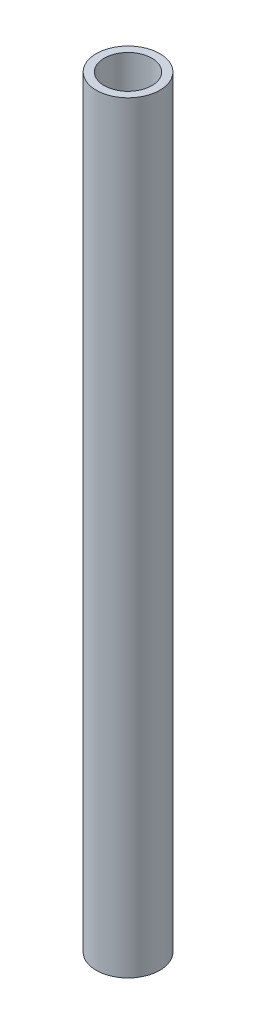
SolidWorks part; units mm, degrees
ref_plane "Front" through (0, 0, 0) normal (0, 0, 1) x (1, 0, 0)
ref_plane "Top" through (0, 0, 0) normal (0, 1, 0) x (1, 0, 0)
ref_plane "Right" through (0, 0, 0) normal (1, 0, 0) x (0, 0, -1)
sketch "Sketch1" plane through (0, 0, 0) normal (0, 1, 0) x (1, 0, 0)
  circle A0 centre (0, 0) radius 25.4
  circle A1 centre (0, 0) radius 19.05
  dimension "D1" = 50.8
  dimension "D2" = 38.1
extrude "Boss-Extrude1" add sketch "Sketch1" along normal blind 609.6
sketch "Sketch2" plane through (0, 0, 0) normal (1, 0, 0) x (0, 0, -1)
  line L0 (0, 609.6) -> (0, 622.3)
  line L1 (19.05, 609.6) -> (-19.05, 609.6) construction
  line L2 (-25.4, 647.7) -> (-228.6, 647.7)
  line L3 (-25.4, 647.7) -> (-25.4, 609.6) construction
  arc A0 (0, 622.3) -> (-25.4, 647.7) centre (-25.4, 622.3) ccw
  dimension "D1" = 12.7
  dimension "D2" = 203.2
sketch "Sketch3" plane through (0, 609.6, 0) normal (0, 1, 0) x (1, 0, 0)
  circle A0 centre (0, 0) radius 19.05 construction
  circle A1 centre (0, 0) radius 25.4
  circle A2 centre (0, 0) radius 25.4
  circle A3 centre (0, 0) radius 19.05
  dimension "D1" = 0
sweep "Sweep1" [suppressed] add profiles "Sketch3" path "Sketch2"
sketch "Sketch4" [suppressed] plane through (0, 304.8, 0) normal (0, 1, 0) x (1, 0, 0)
  circle A0 centre (0, 0) radius 19.05 construction
  circle A1 centre (0, 0) radius 25.4
  circle A2 centre (0, 0) radius 25.4
  circle A3 centre (0, 0) radius 19.05
  dimension "D1" = 0
extrude "Boss-Extrude2" [suppressed] add sketch "Sketch4" along normal blind 914.4
